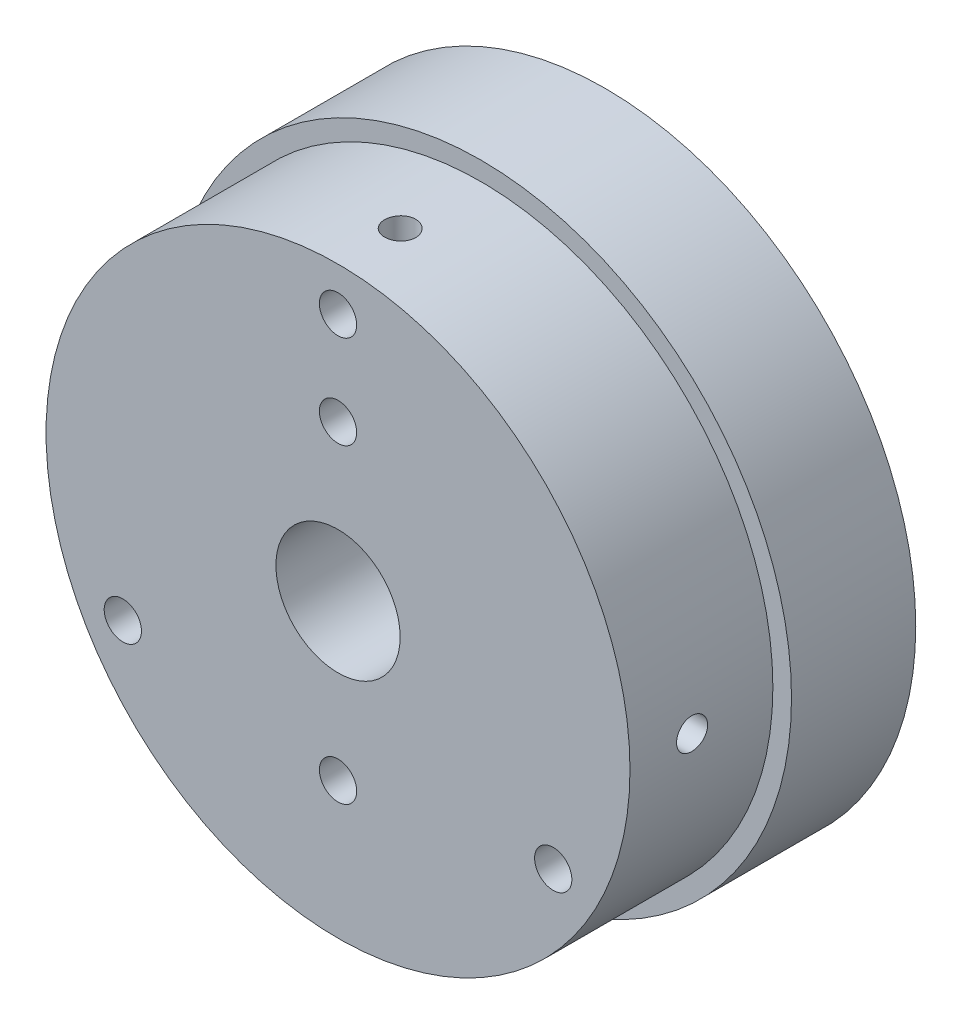
SolidWorks part; units mm, degrees
ref_plane "Front Plane" through (0, 0, 0) normal (0, 0, 1) x (1, 0, 0)
ref_plane "Top Plane" through (0, 0, 0) normal (0, 1, 0) x (1, 0, 0)
ref_plane "Right Plane" through (0, 0, 0) normal (1, 0, 0) x (0, 0, -1)
sketch "Sketch1" plane through (0, 0, 0) normal (0, 0, 1) x (1, 0, 0)
  circle A0 centre (0, 0) radius 50
  dimension "D1" = 100
extrude "Boss-Extrude1" add sketch "Sketch1" along normal blind 20
sketch "Sketch2" plane through (0, 0, 20) normal (0, 0, 1) x (1, 0, 0)
  circle A0 centre (0, 0) radius 47
  dimension "D1" = 94
extrude "Boss-Extrude2" add sketch "Sketch2" along normal blind 23
sketch "Sketch3" plane through (0, 0, 43) normal (0, 0, 1) x (1, 0, 0)
  line L0 (0, 40) -> (0, 0) construction
  line L1 (0, 0) -> (-34.641, -20) construction
  circle A0 centre (0, 0) radius 40 construction
  circle A1 centre (0, 40) radius 3
  circle A2 centre (34.641, -20) radius 3
  circle A3 centre (-34.641, -20) radius 3
  circle A4 centre (0, -25) radius 3
  circle A5 centre (0, 25) radius 3
  circle A6 centre (0, 0) radius 10
  point P11 (0, 0)
  dimension "D1" = 80
  dimension "D2" = 6
  dimension "D5" = 6
  dimension "D6" = 6
  dimension "D9" = 20
  dimension "D4" = 120
  dimension "D7" = 25
  dimension "D8" = 25
  dimension "D3" = 3
extrude "Cut-Extrude1" cut sketch "Sketch3" against normal through all
ref_plane "Plane1" through (50, 0, 0) normal (-1, 0, 0) x (0, 0, 1)
sketch "Sketch5" plane through (50, 0, 0) normal (-1, 0, 0) x (0, 0, 1)
  line L1 (43, -47) -> (43, 47) construction
  circle A0 centre (33, 0) radius 2.5
  dimension "D1" = 5
  dimension "D2" = 10
extrude "Cut-Extrude3" cut sketch "Sketch5" along normal blind 25
pattern_circular "CirPattern1" count 4 over 360 about axis through (0, 0, 43) along (0, 0, -1) of "Cut-Extrude3"
